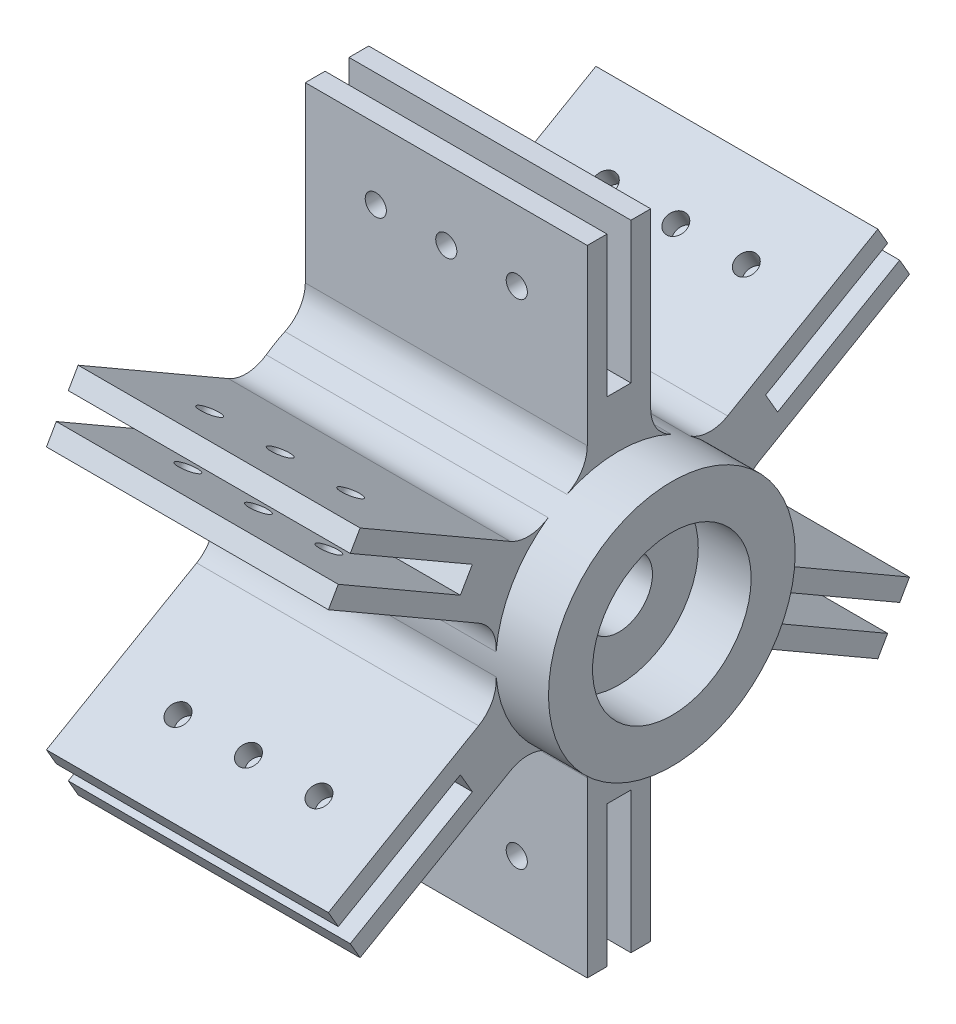
SolidWorks part; units mm, degrees
ref_plane "Front Plane" through (0, 0, 0) normal (0, 0, 1) x (1, 0, 0)
ref_plane "Top Plane" through (0, 0, 0) normal (0, 1, 0) x (1, 0, 0)
ref_plane "Right Plane" through (0, 0, 0) normal (1, 0, 0) x (0, 0, -1)
sketch "Sketch1" plane through (0, 0, 0) normal (1, 0, 0) x (0, 0, -1)
  circle A0 centre (0, 0) radius 17.5
  circle A1 centre (0, 0) radius 4.75
  dimension "D1" = 35
  dimension "D2" = 9.5
extrude "MainBody" add sketch "Sketch1" along normal blind 40
sketch "Sketch2" plane through (40, 0, 0) normal (1, 0, 0) x (0, 0, -1)
  circle A0 centre (0, 0) radius 17.5 construction
  circle A1 centre (0, 0) radius 17.5
  circle A2 centre (0, 0) radius 11.25
  dimension "D1" = 22.5
extrude "BearingHousing" add sketch "Sketch2" along normal blind 7.5
sketch "Sketch3" plane through (0, 0, 0) normal (-1, 0, 0) x (0, 0, 1)
  circle A0 centre (0, 13) radius 1.5
  circle A1 centre (11.2583, 6.5) radius 1.5
  circle A2 centre (11.2583, -6.5) radius 1.5
  circle A3 centre (0, -13) radius 1.5
  circle A4 centre (-11.2583, -6.5) radius 1.5
  circle A5 centre (-11.2583, 6.5) radius 1.5
  point P15 (0, 0)
  dimension "D1" = 3
  dimension "D2" = 13
extrude "MountingHoles" cut sketch "Sketch3" against normal blind 20
sketch "Sketch4" plane through (0, 0, 0) normal (-1, 0, 0) x (0, 0, 1)
  line L0 (0, 0) -> (0, 30) construction
  line L1 (-4.5, 16.9115) -> (-4.5, 45)
  line L2 (-4.5, 45) -> (-1.7, 45)
  line L3 (-1.7, 45) -> (-1.7, 25)
  line L4 (-1.7, 25) -> (1.7, 25)
  line L5 (1.7, 45) -> (1.7, 25)
  line L6 (4.5, 45) -> (1.7, 45)
  line L7 (4.5, 16.9115) -> (4.5, 45)
  circle A0 centre (0, 0) radius 17.5 construction
  arc A1 (4.5, 16.9115) -> (-4.5, 16.9115) centre (0, 0) ccw
  circle A3 centre (0, 0) radius 4.75 construction
  point P9 (0, 45)
  point P11 (0, 25)
  dimension "D1" = 30
  dimension "D2" = 4.5
  dimension "D3" = 45
  dimension "D4" = 1.7
  dimension "D5" = 20
  dimension "D6" = 2.8
extrude "Boss-Extrude3" add sketch "Sketch4" against normal blind 40
sketch "Sketch6" plane through (0, 0, -4.5) normal (0, 0, -1) x (-1, 0, 0)
  line L0 (-40, 45) -> (0, 45) construction
  line L1 (-40, 45) -> (-40, 16.9115) construction
  circle A0 centre (-30, 35) radius 1.5
  circle A1 centre (-20, 35) radius 1.5
  circle A2 centre (-10, 35) radius 1.5
  dimension "D1" = 10
  dimension "D2" = 3
  dimension "D3" = 10
  dimension "D5" = 10
  dimension "D4" = 3
extrude "Cut-Extrude2" cut sketch "Sketch6" against normal blind 10
fillet "Fillet1" radius 5 2 edges at (20, 16.9115, -4.5) (20, 16.9115, 4.5)
pattern_circular "CirPattern1" count 6 over 360 about axis through (0, 0, 0) along (1, 0, 0) of "Boss-Extrude3", "Cut-Extrude2", "Fillet1"
